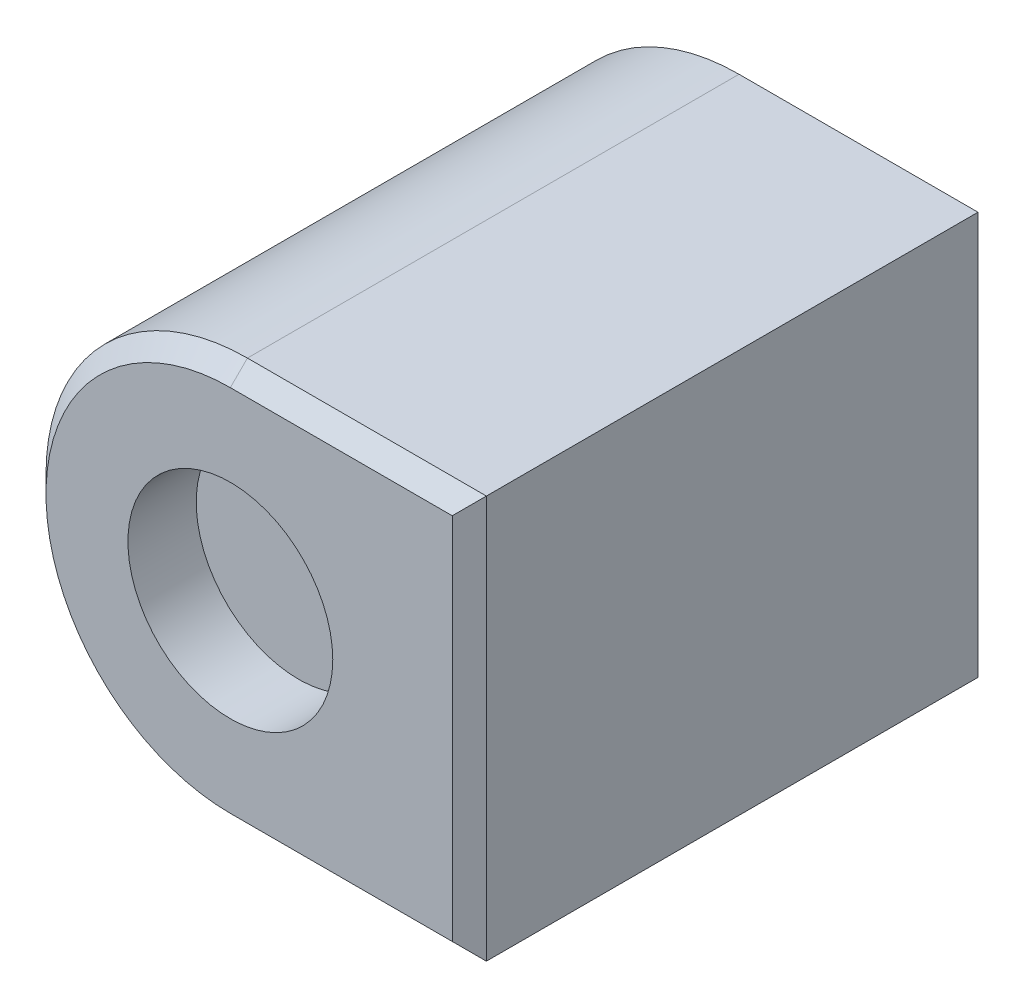
SolidWorks part; units mm, degrees
ref_plane "Alzado" through (0, 0, 0) normal (0, 0, 1) x (1, 0, 0)
ref_plane "Planta" through (0, 0, 0) normal (0, 1, 0) x (1, 0, 0)
ref_plane "Vista lateral" through (0, 0, 0) normal (1, 0, 0) x (0, 0, -1)
sketch "Croquis1" plane through (0, 0, 0) normal (0, 0, 1) x (1, 0, 0)
  line L0 (-59, 0) -> (70, 0) construction
  line L1 (0, 59) -> (70, 59)
  line L2 (70, 59) -> (70, -59)
  line L3 (70, -59) -> (0, -59)
  arc A0 (0, 59) -> (0, -59) centre (0, 0) ccw
  dimension "D1" = 118
  dimension "D2" = 129
extrude "Saliente-Extruir1" add sketch "Croquis1" along normal blind 149
chamfer "Chaflán1" distance 5 angle 45 4 edges at (35, 59, 149) (70, 0, 149) (35, -59, 149) (-59, 0, 149)
sketch "Croquis2" plane through (0, 0, 149) normal (0, 0, 1) x (1, 0, 0)
  circle A0 centre (0, 0) radius 30
  dimension "D1" = 60
extrude "Cortar-Extruir1" cut sketch "Croquis2" against normal blind 20
